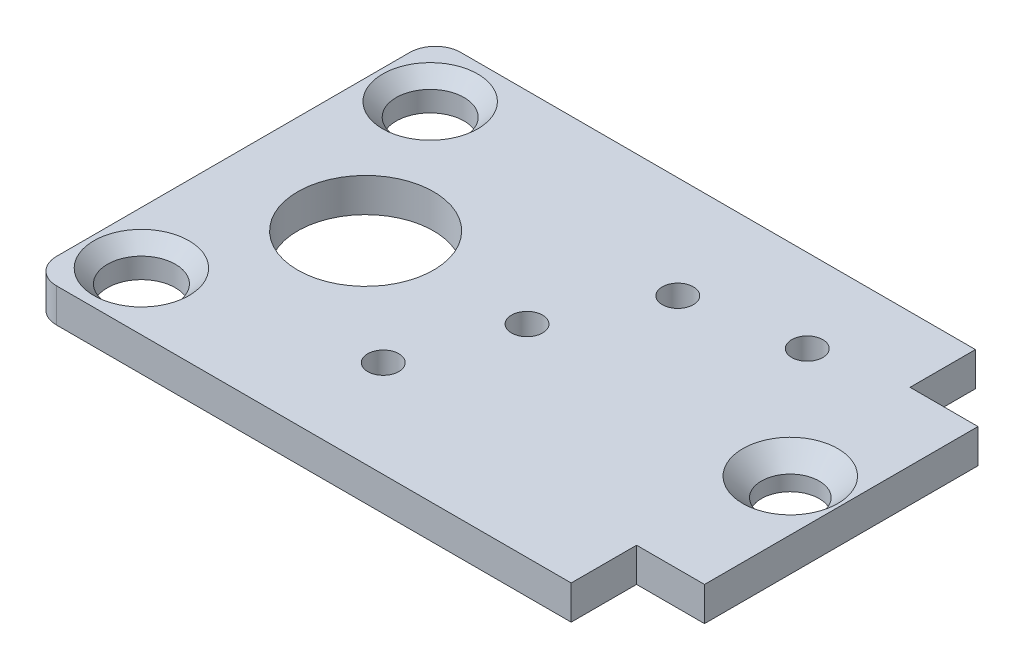
SolidWorks part; units mm, degrees
ref_plane "Front Plane" through (0, 0, 0) normal (0, 0, 1) x (1, 0, 0)
ref_plane "Top Plane" through (0, 0, 0) normal (0, 1, 0) x (1, 0, 0)
ref_plane "Right Plane" through (0, 0, 0) normal (1, 0, 0) x (0, 0, -1)
sketch "Sketch1" plane through (0, 0, 0) normal (0, 1, 0) x (1, 0, 0)
  line L1 (12, 5.95) -> (-3.9, 5.95)
  line L2 (14, 4.025) -> (14, -4.025)
  line L3 (12, -5.95) -> (-3.9, -5.95)
  line L4 (-3.9, 5.95) -> (-3.9, -5.95)
  line L5 (-0.55, 0) -> (0.55, 0) construction
  line L6 (12, 5.95) -> (12, 4.025)
  line L7 (0, -0.55) -> (0, 0.55) construction
  line L8 (12, 4.025) -> (14, 4.025)
  line L9 (12, -5.95) -> (12, -4.025)
  line L10 (12, -4.025) -> (14, -4.025)
  circle A0 centre (0, 0) radius 2
  point P0 (14, 0)
  point P2 (-3.9, 0)
  dimension "D4" = 4
  dimension "D6" = 2
  dimension "D1" = 14
  dimension "D2" = 17.9
  dimension "D3" = 11.9
  dimension "D5" = 8.05
extrude "Boss-Extrude1" add sketch "Sketch1" along normal blind 1
sketch "Sketch2" plane through (0, 1, 0) normal (0, 1, 0) x (1, 0, 0)
  line L0 (-2.35, 4.25) -> (-2.35, -4.25) construction
  line L1 (-0.55, 0) -> (0.55, 0) construction
  line L3 (14, -4.025) -> (14, 4.025) construction
  circle A0 centre (-2.35, 4.25) radius 1
  circle A1 centre (-2.35, -4.25) radius 1
  point P2 (-2.35, 0)
  dimension "D3" = 2
  dimension "D1" = 8.5
  dimension "D2" = 16.35
extrude "Cut-Extrude1" cut sketch "Sketch2" against normal through all
fillet "Fillet1" radius 0.75 2 edges at (-3.9, 0.5, -5.95) (-3.9, 0.5, 5.95)
chamfer "Chamfer1" distance 0.4 angle 45 2 edges at (-2.35, 1, 5.25) (-2.35, 1, -3.25)
sketch "Sketch3" plane through (0, 1, 0) normal (0, 1, 0) x (1, 0, 0)
  line L0 (-0.55, 0) -> (0.55, 0) construction
  line L1 (14, -4.025) -> (14, 4.025) construction
  circle A0 centre (3.6186, -3.1) radius 0.4572
  circle A1 centre (4.75, 0) radius 0.4572
  circle A2 centre (6.2478, 2.9405) radius 0.4572
  circle A3 centre (9.5, 3.5) radius 0.4572
  arc A5 (6.856, 1.5254) -> (6.3481, 4.4776) centre (9.5, 3.5) cw construction
  arc A6 (3.5785, 1.0001) -> (6.2478, -0.3595) centre (6.2478, 2.9405) ccw construction
  arc A7 (5.1489, -3.2758) -> (2.3349, -2.2488) centre (4.75, 0) cw construction
  point P19 (4.75, 0)
  point P22 (3.6186, -3.1)
  point P23 (6.2478, 2.9405)
  dimension "D1" = 0.9144
  dimension "D4" = 3.3
  dimension "D9" = 3.3
  dimension "D10" = 3.3
  dimension "D2" = 3.1
  dimension "D3" = 4.75
  dimension "D5" = 4.5
  dimension "D6" = 7.7522
  dimension "D7" = 10.3814
  dimension "D8" = 3.5
extrude "Cut-Extrude2" cut sketch "Sketch3" against normal through all
hole_wizard "CSK for M1.6 Countersunk Raised Head Screw2" positions "Sketch4" profile "Sketch5" countersink size "M1.6" standard "DIN" end condition through all
sketch "Sketch4" plane through (0, 1, 0) normal (0, 1, 0) x (1, 0, 0)
  line L0 (-0.55, 0) -> (0.55, 0) construction
  line L1 (14, -4.025) -> (14, 4.025) construction
  point P0 (12.5, 0)
  dimension "D1" = 1.5
sketch "Sketch5" plane through (12.5, 1, 0) normal (1, 0, 0) x (0, 0, 1)
  line L0 (0, 0) -> (0, 1)
  line L1 (0, 1) -> (0.85, 1)
  line L2 (0.85, 1) -> (0.85, 0.55)
  line L3 (0.85, 0.55) -> (1.4, 0)
  line L5 (1.4, 0) -> (0, 0)
  line L6 (-0.85, 0.55) -> (-1.4, 0) construction
  line L11 (0, -6.35) -> (0, 107.95) construction
  dimension "Thru Hole Dia." = 1.7
  dimension "Thru Hole Depth" = 1
  dimension "Near C'Sink Dia." = 2.8
  dimension "Near C'Sink Angle" = 90
